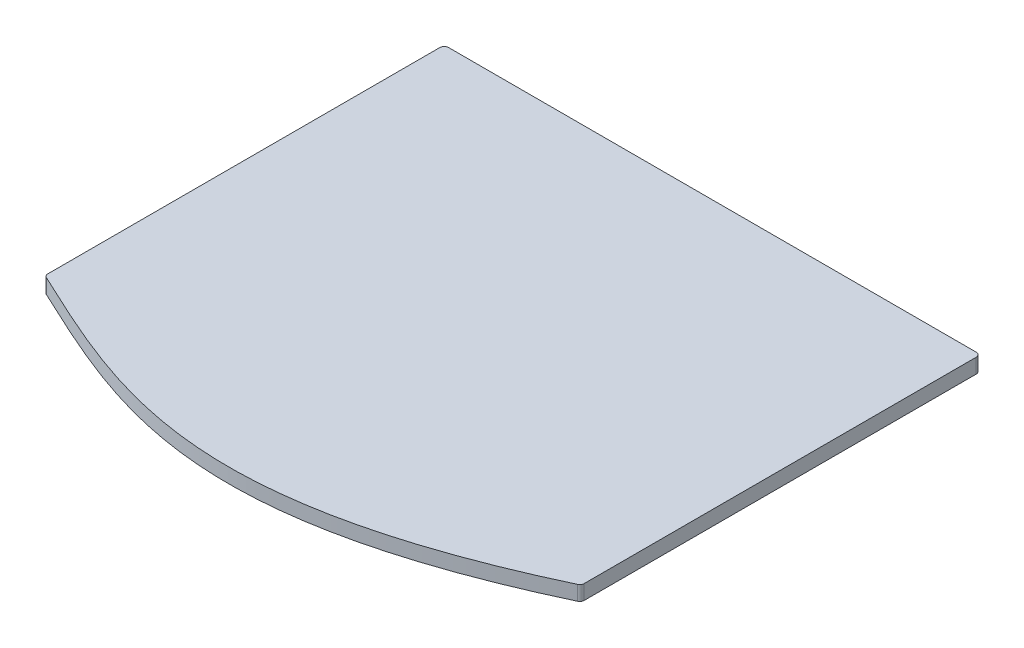
SolidWorks part; units mm, degrees
ref_plane "Front Plane" through (0, 0, 0) normal (0, 0, 1) x (1, 0, 0)
ref_plane "Top Plane" through (0, 0, 0) normal (0, 1, 0) x (1, 0, 0)
ref_plane "Right Plane" through (0, 0, 0) normal (1, 0, 0) x (0, 0, -1)
sketch "Sketch1" plane through (0, 0, 0) normal (0, 1, 0) x (1, 0, 0)
  line L0 (-227.6817, -250) -> (275.4325, -250) construction
  line L5 (-193.2767, 144.9576) -> (183, -137.25) construction
  line L6 (-200, -150) -> (-197.1118, -147.8339) construction
  line L7 (197.1118, -147.8339) -> (200, -150) construction
  line L10 (-183, 130) -> (-183, -137.4808)
  line L11 (183, 130) -> (183, -137.4808)
  line L12 (-180, 133) -> (180, 133)
  line L15 (-183, -137.25) -> (177.3333, 133) construction
  arc A4 (-181.279, -140.1945) -> (-183, -137.4808) centre (-180, -137.4808) cw
  arc A5 (181.279, -140.1945) -> (183, -137.4808) centre (180, -137.4808) ccw
  arc A6 (183, 130) -> (180, 133) centre (180, 130) ccw
  arc A7 (-180, 133) -> (-183, 130) centre (-180, 130) ccw
  spline S2 degree 3 poles (-181.279, -140.1945) (-178.3407, -141.5793) (-172.4539, -144.3539) (-160.746, -149.8289) (-146.1315, -156.5026) (-128.5083, -164.0463) (-104.7027, -173.2541) (-74.017, -182.7441) (-41.0444, -188.464) (-12.5768, -190.1016) (10.0062, -189.6724) (34.0038, -187.388) (59.5895, -183.0397) (82.3695, -177.5175) (101.5437, -171.8528) (116.4173, -166.9539) (131.8012, -161.378) (145.0604, -156.1452) (155.9401, -151.594) (164.2368, -147.9954) (171.271, -144.8375) (176.9615, -142.2188) (179.8451, -140.8703) (181.279, -140.1945) knots 0 0 0 0 0.03125 0.0625 0.125 0.1875 0.25 0.375 0.5 0.5625 0.625 0.6875 0.75 0.8125 0.84375 0.875 0.90625 0.9375 0.953125 0.96875 0.984375 0.992188 1 1 1 1
  point P0 (0, 0)
extrude "Boss-Extrude1" add sketch "Sketch1" along normal blind 10
